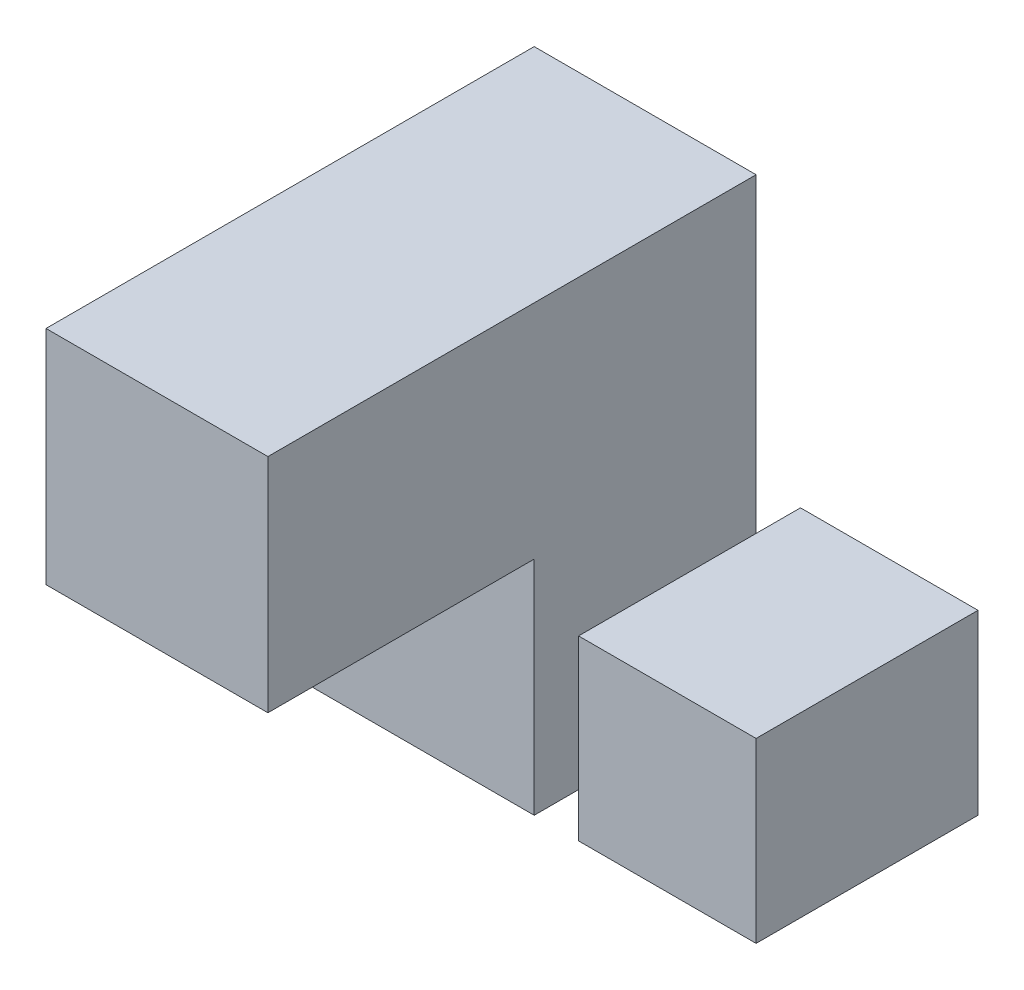
SolidWorks part; units mm, degrees
ref_plane "Front Plane" through (0, 0, 0) normal (0, 0, 1) x (1, 0, 0)
ref_plane "Top Plane" through (0, 0, 0) normal (0, 1, 0) x (1, 0, 0)
ref_plane "Right Plane" through (0, 0, 0) normal (1, 0, 0) x (0, 0, -1)
sketch "Sketch1" plane through (0, 0, 0) normal (0, 0, 1) x (1, 0, 0)
  line L1 (0, 0) -> (10, 0)
  line L2 (0, 0) -> (0, 20)
  line L3 (0, 20) -> (10, 20)
  line L4 (10, 0) -> (10, 20)
extrude "Boss-Extrude1" add sketch "Sketch1" along normal blind 10
sketch "Sketch2" plane through (0, 0, 0) normal (0, 0, 1) x (1, 0, 0)
  line L0 (0, 20) -> (0, 0) construction
  line L1 (0, 10) -> (10, 10)
  line L2 (0, 10) -> (0, 20)
  line L3 (0, 20) -> (10, 20)
  line L4 (10, 10) -> (10, 20)
extrude "Boss-Extrude2" add sketch "Sketch2" along normal blind 22
sketch "Sketch3" plane through (0, 0, 0) normal (0, 0, 1) x (1, 0, 0)
  line L1 (12, 0) -> (20, 0)
  line L2 (12, 0) -> (12, 8)
  line L3 (12, 8) -> (20, 8)
  line L4 (20, 0) -> (20, 8)
extrude "Boss-Extrude3" add sketch "Sketch3" along normal up to vertex (10 mm away) separate body up to point (10, 10, 10)
